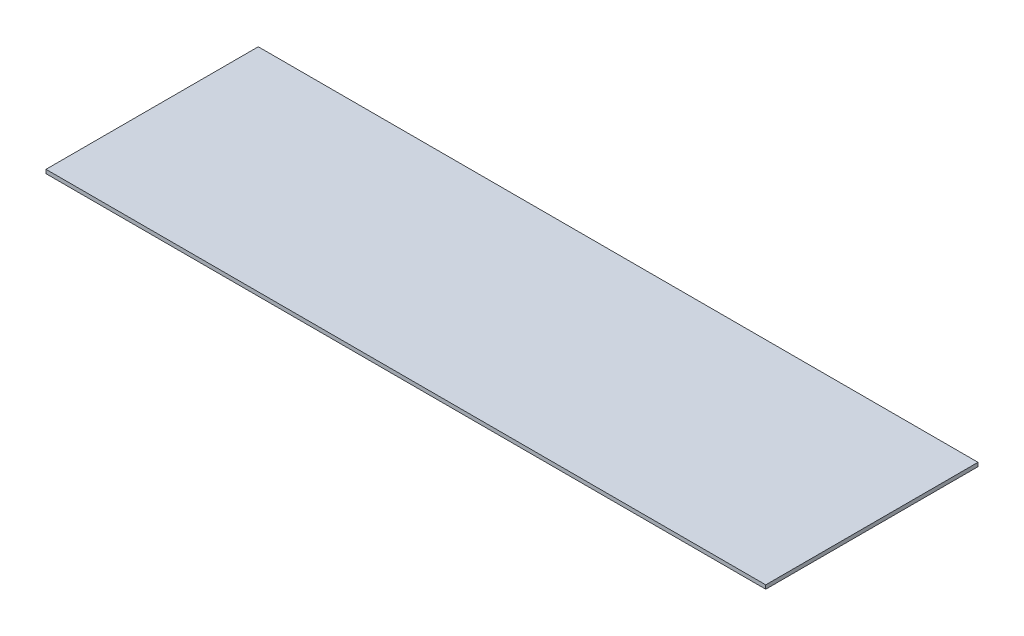
SolidWorks part; units mm, degrees
ref_plane "Front Plane" through (0, 0, 0) normal (0, 0, 1) x (1, 0, 0)
ref_plane "Top Plane" through (0, 0, 0) normal (0, 1, 0) x (1, 0, 0)
ref_plane "Right Plane" through (0, 0, 0) normal (1, 0, 0) x (0, 0, -1)
sketch "Sketch1" plane through (0, 0, 0) normal (0, 1, 0) x (1, 0, 0)
  line L1 (-88.9919, 17.304) -> (1792.9512, 17.304)
  line L2 (-88.9919, 17.304) -> (-88.9919, -537.7164)
  line L3 (-88.9919, -537.7164) -> (1792.9512, -537.7164)
  line L4 (1792.9512, 17.304) -> (1792.9512, -537.7164)
extrude "Boss-Extrude1" add sketch "Sketch1" against normal blind 10
